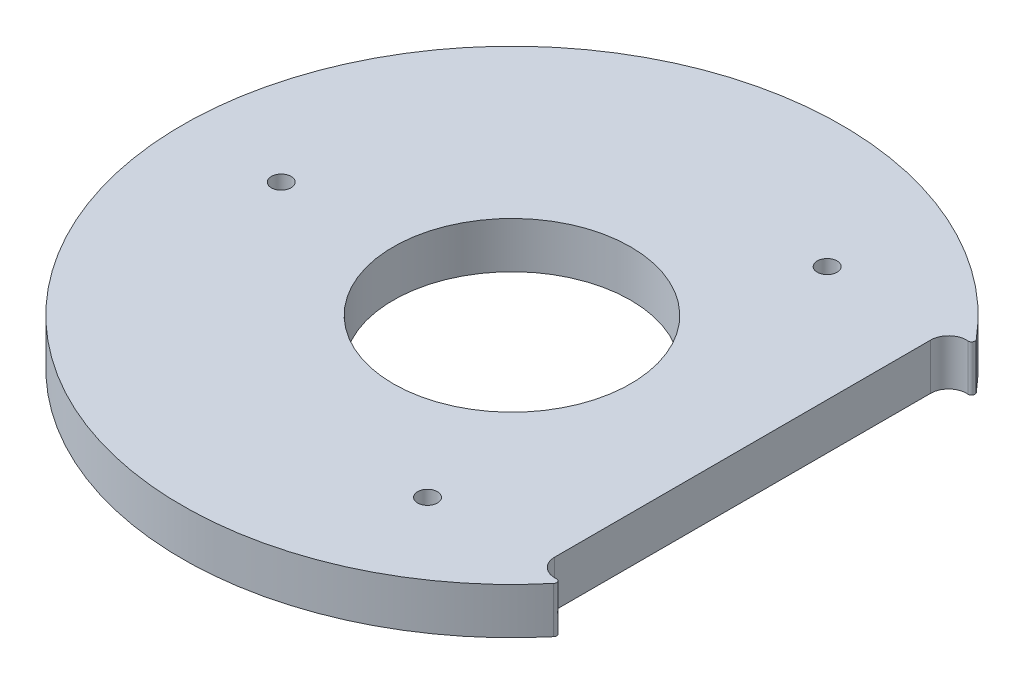
SolidWorks part; units mm, degrees
ref_plane "Alzado" through (0, 0, 0) normal (0, 0, 1) x (1, 0, 0)
ref_plane "Planta" through (0, 0, 0) normal (0, 1, 0) x (1, 0, 0)
ref_plane "Vista lateral" through (0, 0, 0) normal (1, 0, 0) x (0, 0, -1)
sketch "Croquis1" plane through (0, 0, 0) normal (0, 1, 0) x (1, 0, 0)
  line L0 (-50, 0) -> (35, 0) construction
  line L2 (35, 35.7071) -> (35, 64.1896)
  line L3 (35, -28.5161) -> (35, 28.5161)
  arc A0 (38.3792, 32.0474) -> (38.3792, -32.0474) centre (0, 0) ccw
  circle A1 centre (0, 0) radius 18
  arc A2 (37.9494, 31.2228) -> (35, 28.5161) centre (37.7167, 28.5161) ccw
  arc A3 (37.9494, 31.2228) -> (38.3792, 32.0474) centre (37.9926, 31.7246) ccw
  arc A4 (37.9494, -31.2228) -> (38.3792, -32.0474) centre (37.9926, -31.7246) cw
  arc A5 (37.9494, -31.2228) -> (35, -28.5161) centre (37.7167, -28.5161) cw
  dimension "D1" = 100
  dimension "D2" = 36
  dimension "D3" = 85
extrude "Saliente-Extruir1" add sketch "Croquis1" along normal mid plane 7 contours L0 A0 A4 A5 L3 A1 | A0 L0 A1 L3 A2 A3
sketch "Croquis2" plane through (0, -3.5, 0) normal (0, -1, 0) x (1, 0, 0)
  line L0 (0, 0) -> (37.7172, 65.3282) construction
  line L1 (0, 0) -> (37.7172, -65.3282) construction
  line L3 (0, 0) -> (-75.4345, 0) construction
  arc A0 (38.3792, 32.0474) -> (38.3792, -32.0474) centre (0, 0) ccw construction
  arc A1 (38.3792, 32.0474) -> (38.3792, -32.0474) centre (0, 0) ccw
  arc A2 (26.8654, 22.4332) -> (26.8654, -22.4332) centre (0, 0) ccw construction
  circle A3 centre (17.5, 30.3109) radius 1.5
  circle A4 centre (-35, 0) radius 1.5
  circle A5 centre (17.5, -30.3109) radius 1.5
  point P4 (17.5, 30.3109)
  point P5 (17.5, -30.3109)
  point P19 (0, 0)
  dimension "D2" = 3
  dimension "D1" = 15
  dimension "D3" = 3
extrude "Cortar-Extruir1" cut sketch "Croquis2" against normal blind 7 contours A4 | A5 | A3
sketch "Croquis3" plane through (0, -3.5, 0) normal (0, -1, 0) x (1, 0, 0)
  circle A3 centre (17.5, 30.3109) radius 3
  circle A4 centre (17.5, -30.3109) radius 3
  circle A5 centre (-35, 0) radius 3
  circle A6 centre (-35, 0) radius 4
  circle A7 centre (17.5, 30.3109) radius 4
  circle A8 centre (17.5, -30.3109) radius 4
  circle A9 centre (17.5, 30.3109) radius 1.5 construction
  circle A10 centre (17.5, -30.3109) radius 1.5 construction
  dimension "D1" = 8
  dimension "D2" = 6
extrude "Saliente-Extruir2" add sketch "Croquis3" along normal blind 5
sketch "Croquis4" plane through (0, 3.5, 0) normal (0, 1, 0) x (1, 0, 0)
  line L0 (0, 0) -> (38.4392, 31.4918) construction
  line L1 (38.4392, 31.4918) -> (38.3792, -32.0474) construction
  line L2 (38.3792, -32.0474) -> (0, 0) construction
  arc A0 (37.9494, 31.2228) -> (38.3792, 32.0474) centre (37.9926, 31.7246) ccw construction
